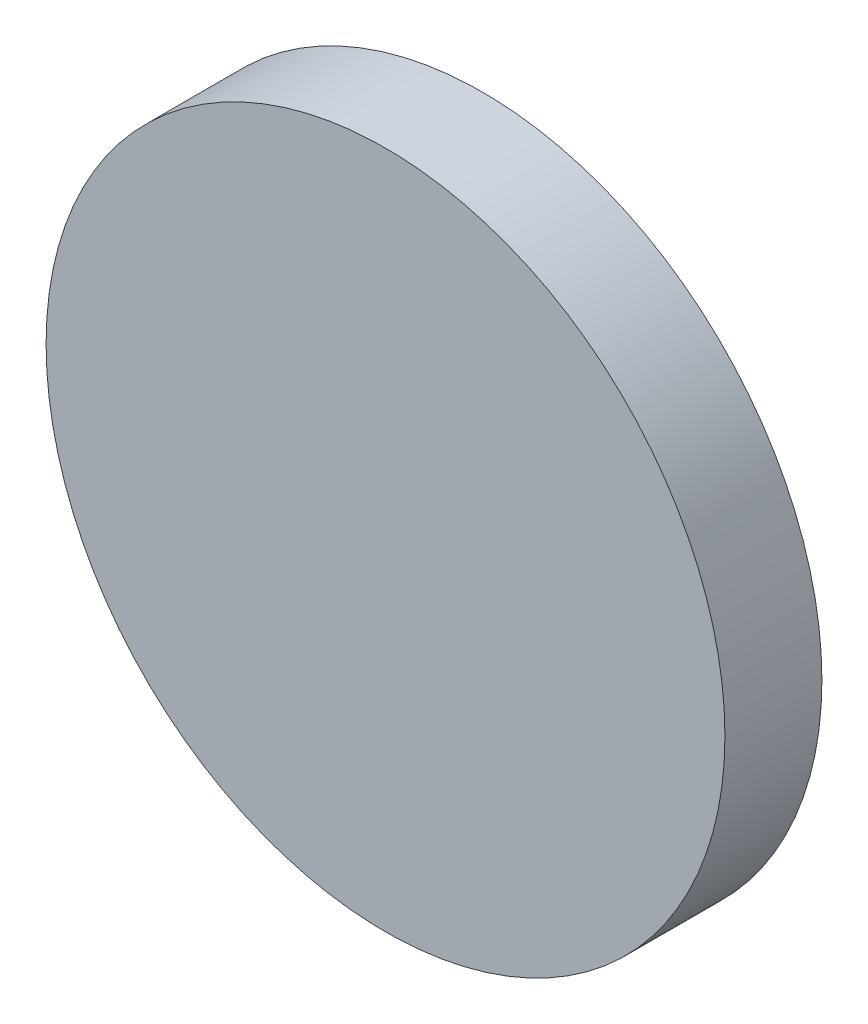
SolidWorks part; units mm, degrees
ref_plane "Front Plane" through (0, 0, 0) normal (0, 0, 1) x (1, 0, 0)
ref_plane "Top Plane" through (0, 0, 0) normal (0, 1, 0) x (1, 0, 0)
ref_plane "Right Plane" through (0, 0, 0) normal (1, 0, 0) x (0, 0, -1)
sketch "Sketch1" plane through (0, 0, 0) normal (0, 0, 1) x (1, 0, 0)
  circle A0 centre (0, 0) radius 7
  dimension "D1" = 14
extrude "Boss-Extrude1" add sketch "Sketch1" along normal blind 2
